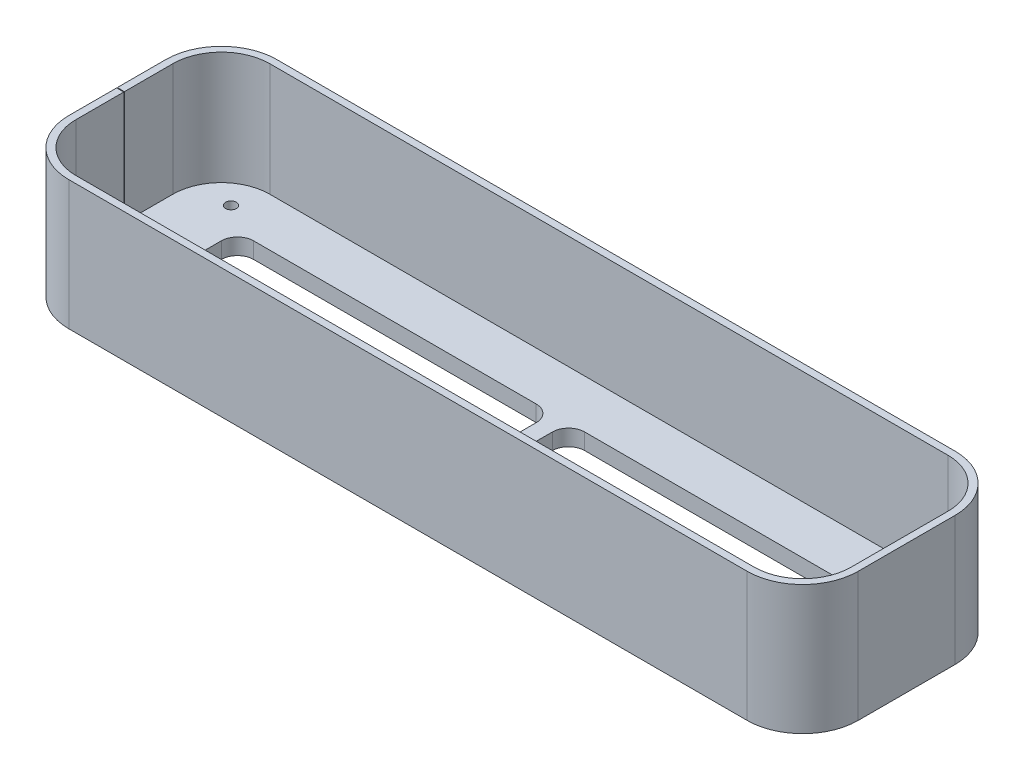
SolidWorks part; units mm, degrees
material "Acrylic (Medium-high impact)"
ref_plane "Front" through (0, 0, 0) normal (0, 0, 1) x (1, 0, 0)
ref_plane "Top" through (0, 0, 0) normal (0, 1, 0) x (1, 0, 0)
ref_plane "Right" through (0, 0, 0) normal (1, 0, 0) x (0, 0, -1)
sketch "Sketch6" [suppressed] plane through (0, 0, 0) normal (0, 0, 1) x (1, 0, 0)
  line L1 (0, 0) -> (730.25, 0)
  line L2 (0, 0) -> (0, -50.8)
  line L3 (0, -50.8) -> (730.25, -50.8)
  line L4 (730.25, 0) -> (730.25, -50.8)
  dimension "D1" = 50.8
  dimension "D2" = 730.25
extrude "Boss-Extrude4" [suppressed] add sketch "Sketch6" along normal blind 2.794
sketch "Sketch1" plane through (0, 0, 0) normal (0, 1, 0) x (1, 0, 0)
  line L1 (-152.4, 38.1) -> (152.4, 38.1)
  line L2 (-152.4, 38.1) -> (-152.4, -38.1)
  line L3 (-152.4, -38.1) -> (152.4, -38.1)
  line L4 (152.4, 38.1) -> (152.4, -38.1)
  line L5 (-152.4, 38.1) -> (152.4, -38.1) construction
  line L6 (-152.4, -38.1) -> (152.4, 38.1) construction
  point P0 (0, 0)
  dimension "D1" = 304.8
  dimension "D2" = 76.2
extrude "Boss-Extrude1" add sketch "Sketch1" along normal blind 6.35
sketch "Sketch2" plane through (0, 6.35, 0) normal (0, 1, 0) x (1, 0, 0)
  line L0 (152.4, -38.1) -> (152.4, 38.1) construction
  line L1 (-127, 19.05) -> (127, 19.05)
  line L2 (-127, 19.05) -> (-127, -19.05)
  line L3 (-127, -19.05) -> (127, -19.05)
  line L4 (127, 19.05) -> (127, -19.05)
  line L5 (-127, 19.05) -> (127, -19.05) construction
  line L6 (-127, -19.05) -> (127, 19.05) construction
  point P0 (0, 0)
  point P6 (127, 0)
  dimension "D1" = 38.1
  dimension "D2" = 25.4
extrude "Cut-Extrude1" cut sketch "Sketch2" against normal through all
sketch "Sketch3" plane through (0, 6.35, 0) normal (0, 1, 0) x (1, 0, 0)
  line L0 (-127, -19.05) -> (127, -19.05) construction
  line L1 (-3.175, 19.05) -> (3.175, 19.05)
  line L2 (-3.175, 19.05) -> (-3.175, -19.05)
  line L3 (-3.175, -19.05) -> (3.175, -19.05)
  line L4 (3.175, 19.05) -> (3.175, -19.05)
  line L5 (-3.175, 19.05) -> (3.175, -19.05) construction
  line L6 (-3.175, -19.05) -> (3.175, 19.05) construction
  point P0 (0, 0)
  dimension "D1" = 6.35
extrude "Boss-Extrude2" add sketch "Sketch3" against normal up to surface (6.35 mm away) up to face at (0, 0, 0)
fillet "Fillet1" radius 19.05 4 edges at (152.4, 3.175, -38.1) (152.4, 3.175, 38.1) (-152.4, 3.175, 38.1) (-152.4, 3.175, -38.1)
fillet "Fillet2" radius 6.35 8 edges at (3.175, 3.175, 19.05) (3.175, 3.175, -19.05) (127, 3.175, -19.05) (127, 3.175, 19.05) (-3.175, 3.175, 19.05) (-3.175, 3.175, -19.05) (-127, 3.175, -19.05) (-127, 3.175, 19.05)
sketch "Sketch4" plane through (0, 6.35, 0) normal (0, 1, 0) x (1, 0, 0)
  line L0 (133.35, 38.1) -> (-133.35, 38.1) construction
  line L1 (-137.16, 26.67) -> (137.16, 26.67) construction
  line L2 (-137.16, 26.67) -> (-137.16, -26.67) construction
  line L3 (-137.16, -26.67) -> (137.16, -26.67) construction
  line L4 (137.16, 26.67) -> (137.16, -26.67) construction
  line L5 (-137.16, 26.67) -> (137.16, -26.67) construction
  line L6 (-137.16, -26.67) -> (137.16, 26.67) construction
  line L7 (152.4, -19.05) -> (152.4, 19.05) construction
  circle A0 centre (137.16, 26.67) radius 2.14
  circle A1 centre (137.16, -26.67) radius 2.14
  circle A2 centre (-137.16, -26.67) radius 2.14
  circle A3 centre (-137.16, 26.67) radius 2.14
  point P0 (0, 0)
  dimension "D3" = 4.2799
  dimension "D1" = 11.43
  dimension "D2" = 15.24
extrude "Cut-Extrude2" cut sketch "Sketch4" against normal through all
sketch "Sketch5" plane through (0, 0, 0) normal (0, 1, 0) x (1, 0, 0)
  line L0 (-155.194, 19.05) -> (-155.194, 0)
  line L1 (-133.35, -40.894) -> (133.35, -40.894)
  line L2 (155.194, -19.05) -> (155.194, 19.05)
  line L3 (133.35, 40.894) -> (-133.35, 40.894)
  line L4 (152.4, -19.05) -> (152.4, 19.05)
  line L5 (133.35, 38.1) -> (-133.35, 38.1)
  line L6 (-152.4, 19.05) -> (-152.4, -19.05)
  line L7 (-133.35, -38.1) -> (133.35, -38.1)
  line L8 (152.4, -19.05) -> (152.4, 19.05)
  line L9 (133.35, 38.1) -> (-133.35, 38.1)
  line L10 (-152.4, 19.05) -> (-152.4, 0)
  line L11 (-133.35, -38.1) -> (133.35, -38.1)
  line L12 (-152.4, 0) -> (-155.194, 0)
  line L13 (-152.4, -0.254) -> (-155.194, -0.254)
  line L14 (-155.194, -0.254) -> (-155.194, -19.05)
  line L15 (-155.194, 19.05) -> (-155.194, -19.05) construction
  line L16 (-152.4, -0.254) -> (-152.4, -19.05)
  line L17 (-152.4, 19.05) -> (-152.4, -19.05) construction
  arc A0 (-133.35, 40.894) -> (-155.194, 19.05) centre (-133.35, 19.05) ccw
  arc A1 (-155.194, -19.05) -> (-133.35, -40.894) centre (-133.35, -19.05) ccw
  arc A2 (133.35, -40.894) -> (155.194, -19.05) centre (133.35, -19.05) ccw
  arc A3 (155.194, 19.05) -> (133.35, 40.894) centre (133.35, 19.05) ccw
  arc A4 (152.4, 19.05) -> (133.35, 38.1) centre (133.35, 19.05) ccw
  arc A5 (-133.35, 38.1) -> (-152.4, 19.05) centre (-133.35, 19.05) ccw
  arc A6 (-152.4, -19.05) -> (-133.35, -38.1) centre (-133.35, -19.05) ccw
  arc A7 (133.35, -38.1) -> (152.4, -19.05) centre (133.35, -19.05) ccw
  arc A8 (152.4, 19.05) -> (133.35, 38.1) centre (133.35, 19.05) ccw
  arc A9 (-133.35, 38.1) -> (-152.4, 19.05) centre (-133.35, 19.05) ccw
  arc A10 (-152.4, -19.05) -> (-133.35, -38.1) centre (-133.35, -19.05) ccw
  arc A11 (133.35, -38.1) -> (152.4, -19.05) centre (133.35, -19.05) ccw
  dimension "D3" = 0.254
  dimension "D4" = 38.1
  dimension "D1" = 0
  dimension "D2" = 2.794
extrude "Boss-Extrude3" add sketch "Sketch5" along normal blind 50.8 separate body
